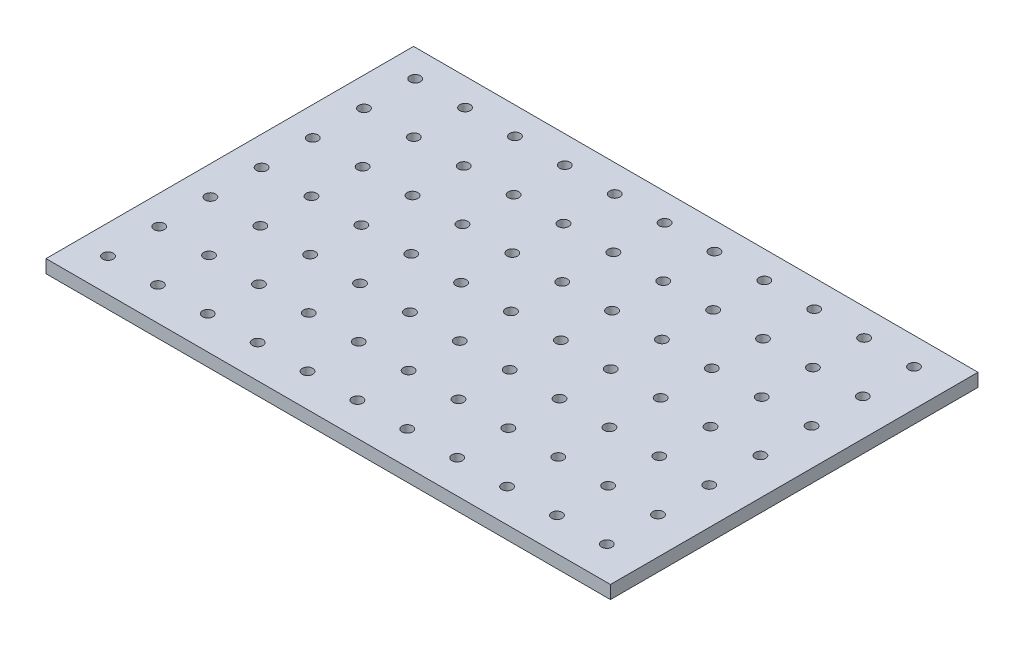
SolidWorks part; units mm, degrees
ref_plane "Front Plane" through (0, 0, 0) normal (0, 0, 1) x (1, 0, 0)
ref_plane "Top Plane" through (0, 0, 0) normal (0, 1, 0) x (1, 0, 0)
ref_plane "Right Plane" through (0, 0, 0) normal (1, 0, 0) x (0, 0, -1)
sketch "Sketch1" plane through (0, 0, 0) normal (0, 1, 0) x (1, 0, 0)
  line L1 (-61.9653, 45.6647) -> (153.0347, 45.6647)
  line L2 (-61.9653, 45.6647) -> (-61.9653, -94.3353)
  line L3 (-61.9653, -94.3353) -> (153.0347, -94.3353)
  line L4 (153.0347, 45.6647) -> (153.0347, -94.3353)
  dimension "D1" = 140
  dimension "D2" = 215
extrude "Boss-Extrude1" add sketch "Sketch1" along normal blind 5
sketch "Sketch2" plane through (0, 5, 0) normal (0, 1, 0) x (1, 0, 0)
  line L0 (-61.9653, 45.6647) -> (-61.9653, -94.3353) construction
  circle A0 centre (-50.9653, 35.2789) radius 2
  circle A1 centre (-31.9653, 35.2789) radius 2
  circle A2 centre (-12.9653, 35.2789) radius 2
  circle A3 centre (6.0347, 35.2789) radius 2
  circle A4 centre (25.0347, 35.2789) radius 2
  circle A5 centre (44.0347, 35.2789) radius 2
  circle A6 centre (63.0347, 35.2789) radius 2
  circle A7 centre (82.0347, 35.2789) radius 2
  circle A8 centre (101.0347, 35.2789) radius 2
  circle A9 centre (120.0347, 35.2789) radius 2
  circle A10 centre (139.0347, 35.2789) radius 2
  circle A11 centre (-50.9653, 15.7789) radius 2
  circle A12 centre (-31.9653, 15.7789) radius 2
  circle A13 centre (-12.9653, 15.7789) radius 2
  circle A14 centre (6.0347, 15.7789) radius 2
  circle A15 centre (25.0347, 15.7789) radius 2
  circle A16 centre (44.0347, 15.7789) radius 2
  circle A17 centre (63.0347, 15.7789) radius 2
  circle A18 centre (82.0347, 15.7789) radius 2
  circle A19 centre (101.0347, 15.7789) radius 2
  circle A20 centre (120.0347, 15.7789) radius 2
  circle A21 centre (139.0347, 15.7789) radius 2
  circle A22 centre (-50.9653, -3.7211) radius 2
  circle A23 centre (-31.9653, -3.7211) radius 2
  circle A24 centre (-12.9653, -3.7211) radius 2
  circle A25 centre (6.0347, -3.7211) radius 2
  circle A26 centre (25.0347, -3.7211) radius 2
  circle A27 centre (44.0347, -3.7211) radius 2
  circle A28 centre (63.0347, -3.7211) radius 2
  circle A29 centre (82.0347, -3.7211) radius 2
  circle A30 centre (101.0347, -3.7211) radius 2
  circle A31 centre (120.0347, -3.7211) radius 2
  circle A32 centre (139.0347, -3.7211) radius 2
  circle A33 centre (-50.9653, -23.2211) radius 2
  circle A34 centre (-31.9653, -23.2211) radius 2
  circle A35 centre (-12.9653, -23.2211) radius 2
  circle A36 centre (6.0347, -23.2211) radius 2
  circle A37 centre (25.0347, -23.2211) radius 2
  circle A38 centre (44.0347, -23.2211) radius 2
  circle A39 centre (63.0347, -23.2211) radius 2
  circle A40 centre (82.0347, -23.2211) radius 2
  circle A41 centre (101.0347, -23.2211) radius 2
  circle A42 centre (120.0347, -23.2211) radius 2
  circle A43 centre (139.0347, -23.2211) radius 2
  circle A44 centre (-50.9653, -42.7211) radius 2
  circle A45 centre (-31.9653, -42.7211) radius 2
  circle A46 centre (-12.9653, -42.7211) radius 2
  circle A47 centre (6.0347, -42.7211) radius 2
  circle A48 centre (25.0347, -42.7211) radius 2
  circle A49 centre (44.0347, -42.7211) radius 2
  circle A50 centre (63.0347, -42.7211) radius 2
  circle A51 centre (82.0347, -42.7211) radius 2
  circle A52 centre (101.0347, -42.7211) radius 2
  circle A53 centre (120.0347, -42.7211) radius 2
  circle A54 centre (139.0347, -42.7211) radius 2
  circle A55 centre (-50.9653, -62.2211) radius 2
  circle A56 centre (-31.9653, -62.2211) radius 2
  circle A57 centre (-12.9653, -62.2211) radius 2
  circle A58 centre (6.0347, -62.2211) radius 2
  circle A59 centre (25.0347, -62.2211) radius 2
  circle A60 centre (44.0347, -62.2211) radius 2
  circle A61 centre (63.0347, -62.2211) radius 2
  circle A62 centre (82.0347, -62.2211) radius 2
  circle A63 centre (101.0347, -62.2211) radius 2
  circle A64 centre (120.0347, -62.2211) radius 2
  circle A65 centre (139.0347, -62.2211) radius 2
  circle A66 centre (-50.9653, -81.7211) radius 2
  circle A67 centre (-31.9653, -81.7211) radius 2
  circle A68 centre (-12.9653, -81.7211) radius 2
  circle A69 centre (6.0347, -81.7211) radius 2
  circle A70 centre (25.0347, -81.7211) radius 2
  circle A71 centre (44.0347, -81.7211) radius 2
  circle A72 centre (63.0347, -81.7211) radius 2
  circle A73 centre (82.0347, -81.7211) radius 2
  circle A74 centre (101.0347, -81.7211) radius 2
  circle A75 centre (120.0347, -81.7211) radius 2
  circle A76 centre (139.0347, -81.7211) radius 2
  dimension "D1" = 4
  dimension "D2" = 11
  dimension "D3" = 11
  dimension "D4" = 7
extrude "Cut-Extrude1" cut sketch "Sketch2" against normal blind 5
